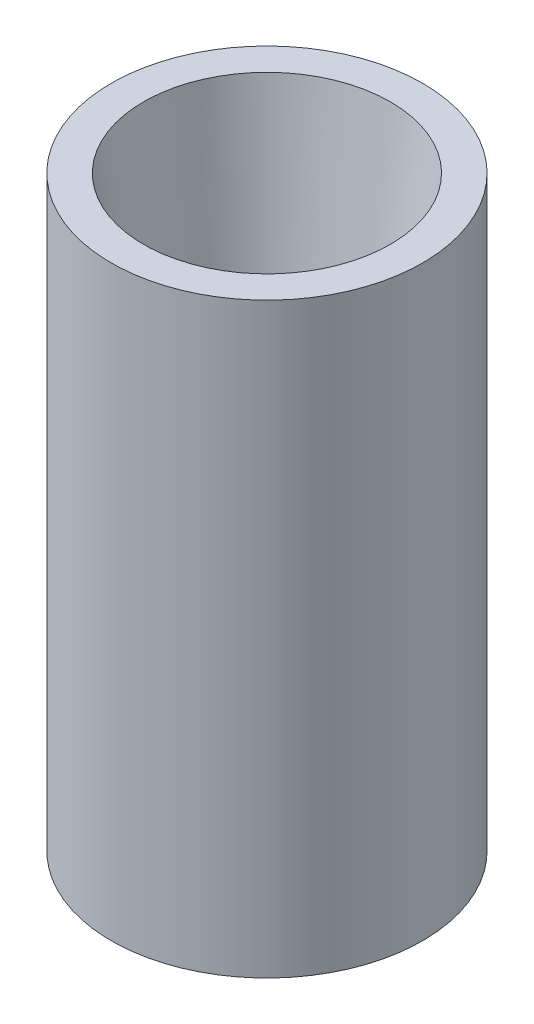
SolidWorks part; units mm, degrees
ref_plane "Front Plane" through (0, 0, 0) normal (0, 0, 1) x (1, 0, 0)
ref_plane "Top Plane" through (0, 0, 0) normal (0, 1, 0) x (1, 0, 0)
ref_plane "Right Plane" through (0, 0, 0) normal (1, 0, 0) x (0, 0, -1)
sketch "Sketch1" plane through (0, 0, 0) normal (0, 0, 1) x (1, 0, 0)
  line L1 (-43.5, -7) -> (-43.5, 157.0441)
  line L2 (-43.5, 157.0441) -> (-34.5, 157.0441)
  line L3 (-34.5, 157.0441) -> (-20.5, 55)
  line L4 (-20.5, 55) -> (-20.5, 5)
  line L5 (-20.5, 5) -> (0, 5)
  line L7 (0, 0) -> (0, 175.5796) construction
  line L10 (-18.034, -7) -> (-43.5, -7)
  line L11 (-18.034, -7) -> (-18.034, 2)
  line L12 (-18.034, 2) -> (0, 2)
  line L13 (0, 2) -> (0, 5)
  dimension "D1" = 9
  dimension "D2" = 34.5
  dimension "D3" = 20.5
  dimension "D4" = 103
  dimension "D5" = 9
  dimension "D6" = 3
  dimension "D7" = 2
  dimension "D8" = 50
  dimension "D9" = 18.034
revolve "Revolve1" add sketch "Sketch1" angle 360 about L7
